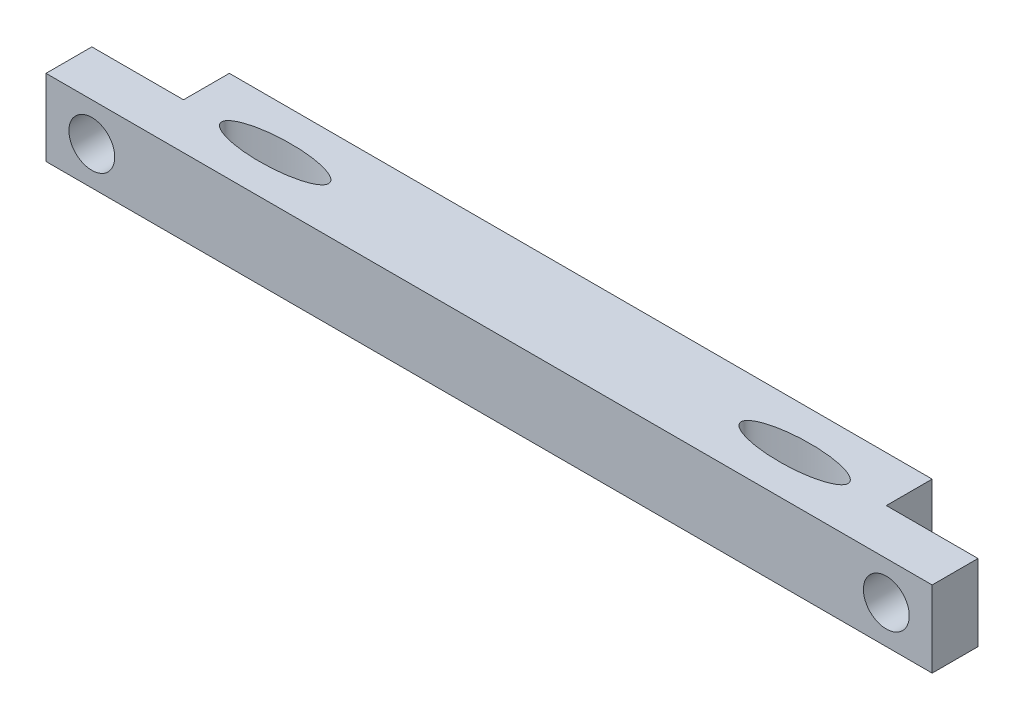
SolidWorks part; units mm, degrees
ref_plane "Front Plane" through (0, 0, 0) normal (0, 0, 1) x (1, 0, 0)
ref_plane "Top Plane" through (0, 0, 0) normal (0, 1, 0) x (1, 0, 0)
ref_plane "Right Plane" through (0, 0, 0) normal (1, 0, 0) x (0, 0, -1)
ref_plane "Plane1" through (0, -5, 0) normal (0, -1, 0) x (1, 0, 0)
sketch "Sketch1" plane through (0, -5, 0) normal (0, -1, 0) x (1, 0, 0)
  line L0 (-58, -6) -> (58, -6)
  line L1 (58, -6) -> (58, 6)
  line L2 (58, 6) -> (-58, 6)
  line L3 (-58, 6) -> (-58, -6)
extrude "Boss-Extrude1" add sketch "Sketch1" against normal blind 10
sketch "Sketch2" plane through (0, 5, 0) normal (0, 1, 0) x (-1, 0, 0)
  line L0 (58, -6) -> (58, 0)
  line L1 (58, 0) -> (46, 0)
  line L2 (46, 0) -> (46, -6)
  line L3 (46, -6) -> (58, -6)
extrude "Cut-Extrude1" cut sketch "Sketch2" against normal through all
sketch "Sketch3" plane through (0, 5, 0) normal (0, 1, 0) x (-1, 0, 0)
  line L0 (-46, -6) -> (-46, 0)
  line L1 (-46, 0) -> (-58, 0)
  line L2 (-58, 0) -> (-58, -6)
  line L3 (-58, -6) -> (-46, -6)
extrude "Cut-Extrude2" cut sketch "Sketch3" against normal through all
sketch "Sketch4" plane through (0, -5, 0) normal (0, -1, 0) x (1, 0, 0)
  line L50 (27, 0) -> (41, 0) construction
  line L51 (34, -2.0376) -> (34, 2.0376) construction
  ellipse E0 centre (34, 0) end of major axis (41, 0) minor radius 2.0376
extrude "Cut-Extrude3" cut sketch "Sketch4" against normal through all
sketch "Sketch5" plane through (0, 0, 0) normal (0, 0, -1) x (-1, 0, 0)
  line L50 (51.8116, -2.9941) -> (52.1884, 2.9941) construction
  circle A0 centre (52, 0) radius 3
extrude "Cut-Extrude4" cut sketch "Sketch5" against normal through all
sketch "Sketch6" plane through (0, 0, 0) normal (0, 0, -1) x (-1, 0, 0)
  line L50 (-51.8116, 2.9941) -> (-52.1884, -2.9941) construction
  circle A0 centre (-52, 0) radius 3
extrude "Cut-Extrude5" cut sketch "Sketch6" against normal through all
sketch "Sketch7" plane through (0, 5, 0) normal (0, 1, 0) x (-1, 0, 0)
  line L50 (41, 0) -> (27, 0) construction
  line L51 (34, -2.0376) -> (34, 2.0376) construction
  ellipse E0 centre (34, 0) end of major axis (41, 0) minor radius 2.0376
extrude "Cut-Extrude6" cut sketch "Sketch7" against normal through all
